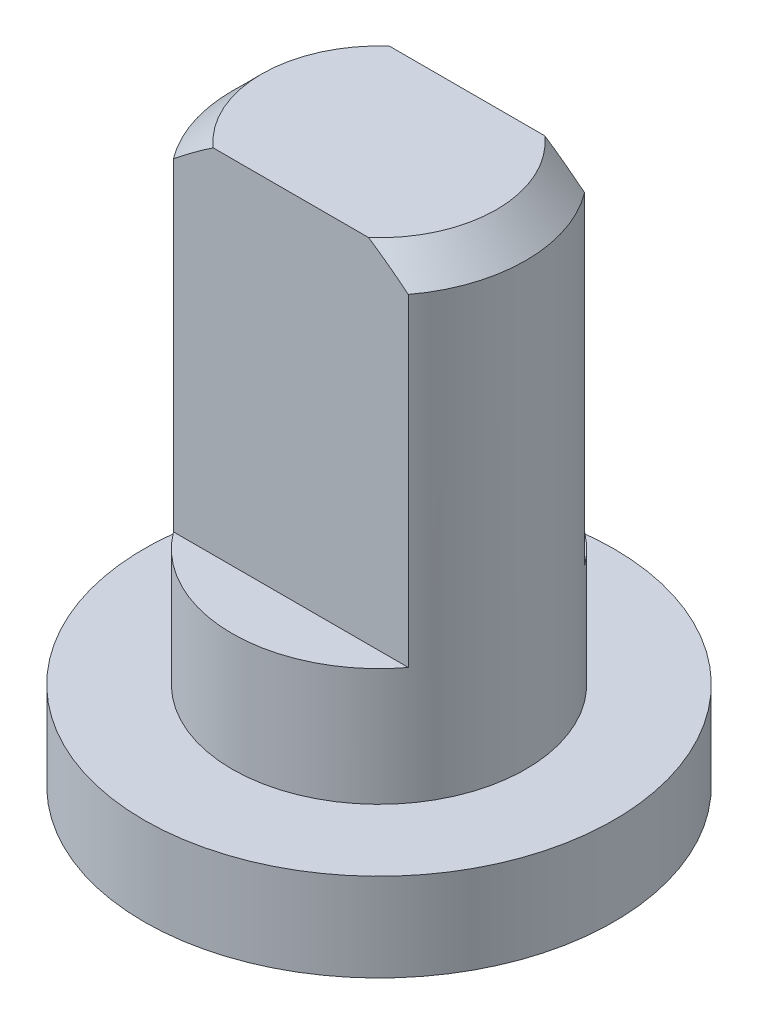
SolidWorks part; units mm, degrees
ref_plane "前视基准面" through (0, 0, 0) normal (0, 0, 1) x (1, 0, 0)
ref_plane "上视基准面" through (0, 0, 0) normal (0, 1, 0) x (1, 0, 0)
ref_plane "右视基准面" through (0, 0, 0) normal (1, 0, 0) x (0, 0, -1)
other "Configuration Table"
sketch "草图1" plane through (0, 0, 0) normal (0, 1, 0) x (1, 0, 0)
  circle A0 centre (0, 0) radius 4
  dimension "D1" = 8
extrude "凸台-拉伸1" add sketch "草图1" along normal blind 1.5
sketch "草图3" plane through (0, 1.5, 0) normal (0, 1, 0) x (1, 0, 0)
  circle A0 centre (0, 0) radius 2.5
  dimension "D1" = 5
extrude "凸台-拉伸3" add sketch "草图3" along normal blind 2
sketch "草图2" plane through (0, 3.5, 0) normal (0, 1, 0) x (1, 0, 0)
  line L0 (-2, 1.5) -> (2, 1.5)
  line L1 (-2.5, 0) -> (2.5, 0) construction
  line L2 (-2, -1.5) -> (2, -1.5)
  arc A0 (-2, 1.5) -> (-2, -1.5) centre (0, 0) ccw
  arc A1 (2, -1.5) -> (2, 1.5) centre (0, 0) ccw
  dimension "D1" = 5
  dimension "D2" = 3
extrude "凸台-拉伸2" add sketch "草图2" along normal blind 6
chamfer "倒角1" distance 0.5 angle 45 2 edges at (-2.5, 9.5, 0) (2.5, 9.5, 0)
